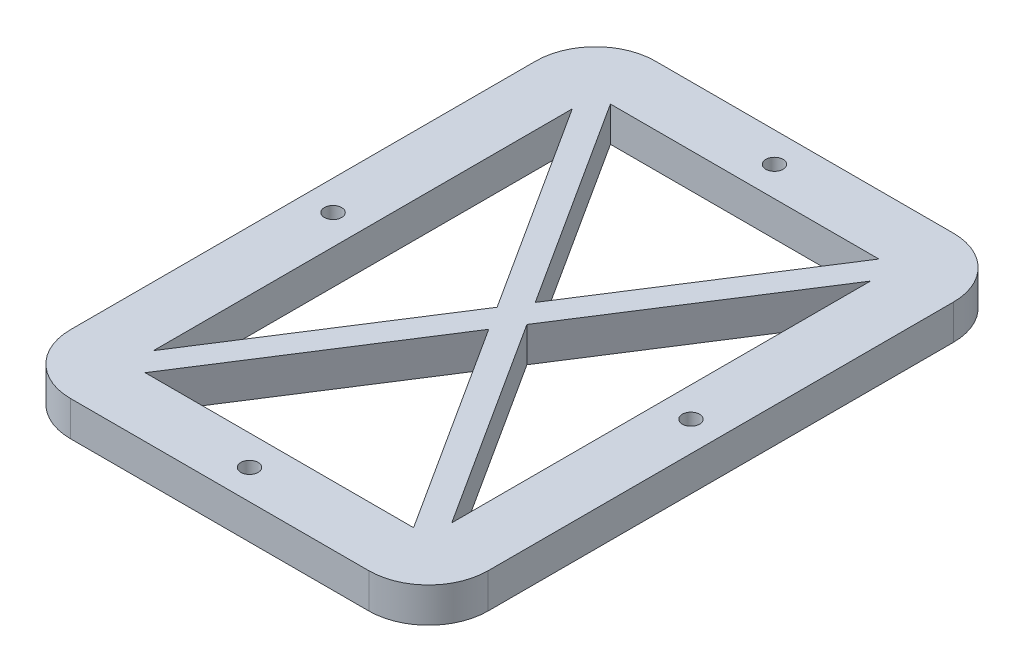
SolidWorks part; units mm, degrees
material "Acrylic (Medium-high impact)"
ref_plane "Front Plane" through (0, 0, 0) normal (0, 0, 1) x (1, 0, 0)
ref_plane "Top Plane" through (0, 0, 0) normal (0, 1, 0) x (1, 0, 0)
ref_plane "Right Plane" through (0, 0, 0) normal (1, 0, 0) x (0, 0, -1)
sketch "Sketch1" plane through (0, 0, 0) normal (0, 1, 0) x (1, 0, 0)
  line L0 (-35, 49) -> (-35, -49) construction
  line L1 (-35, 49) -> (35, 49) construction
  line L2 (-35, -49) -> (35, -49) construction
  line L3 (35, 49) -> (35, -49) construction
  line L4 (-27.5, -39) -> (-22.5, -39)
  line L5 (-27.5, -39) -> (22.5, 39)
  line L6 (-55, 0) -> (55, 0) construction
  line L7 (-74.55, 39) -> (60.5097, 39) construction
  line L8 (-25, 39) -> (25, 39)
  line L9 (-25, 39) -> (-25, -39)
  line L10 (-25, -39) -> (25, -39)
  line L11 (25, 39) -> (25, -39)
  line L12 (-25, 39) -> (25, -39) construction
  line L13 (-25, -39) -> (25, 39) construction
  line L14 (-71.5261, -39) -> (60.5097, -39) construction
  line L15 (-35, 39) -> (-35, -39)
  line L16 (-25, -996.6512) -> (-25, 49003.3488) construction
  line L17 (25, -1000) -> (25, 49000) construction
  line L18 (-25, 49) -> (25, 49)
  line L19 (35, 39) -> (35, -39)
  line L20 (-25, -49) -> (25, -49)
  line L21 (-62.4665, 0) -> (49937.5335, 0) construction
  line L22 (0, 0) -> (0, 50000) construction
  line L23 (-22.5, -39) -> (27.5, 39)
  line L24 (22.5, 39) -> (27.5, 39)
  line L25 (27.5, -39) -> (22.5, -39)
  line L26 (27.5, -39) -> (-22.5, 39)
  line L27 (22.5, -39) -> (-27.5, 39)
  line L28 (-22.5, 39) -> (-27.5, 39)
  arc A0 (-35, 39) -> (-25, 49) centre (-25, 39) cw
  arc A1 (25, 49) -> (35, 39) centre (25, 39) cw
  arc A2 (35, -39) -> (25, -49) centre (25, -39) cw
  arc A3 (-25, -49) -> (-35, -39) centre (-25, -39) cw
  circle A4 centre (0, 44) radius 1.45
  circle A5 centre (0, -44) radius 1.45
  circle A6 centre (-30, 0) radius 1.45
  circle A7 centre (30, 0) radius 1.45
  point P1 (0, 0)
  point P3 (0, 0)
  point P24 (25, 0)
  point P25 (35, 39)
  point P26 (35, -39)
  point P27 (-25, 49)
  point P28 (25, 49)
  point P34 (25, -49)
  point P35 (-25, -49)
  dimension "D6" = 5
  dimension "D7" = 2.9
  dimension "D10" = 30
  dimension "D11" = 2.9
  dimension "D1" = 98
  dimension "D2" = 70
  dimension "D3" = 78
  dimension "D4" = 50
  dimension "D5" = 5
extrude "Boss-Extrude1" add sketch "Sketch1" along normal blind 5.85 contours A3 L20 A2 L19 A1 L18 A0 L15 A7 A6 A5 A4 L28 L8 L24 L23 L11 L26 L25 L10 L4 L5 L9 L27 | L23 L27 L5 L9 L4 | L27 L5 L26 L8 L9 | L9 L28 L27 | L9 L5 L4 | L25 L26 L11 | L27 L10 L11 L26 L23 | L27 L23 L26 L5 | L26 L23 L11 L8 L5 | L24 L11 L23
